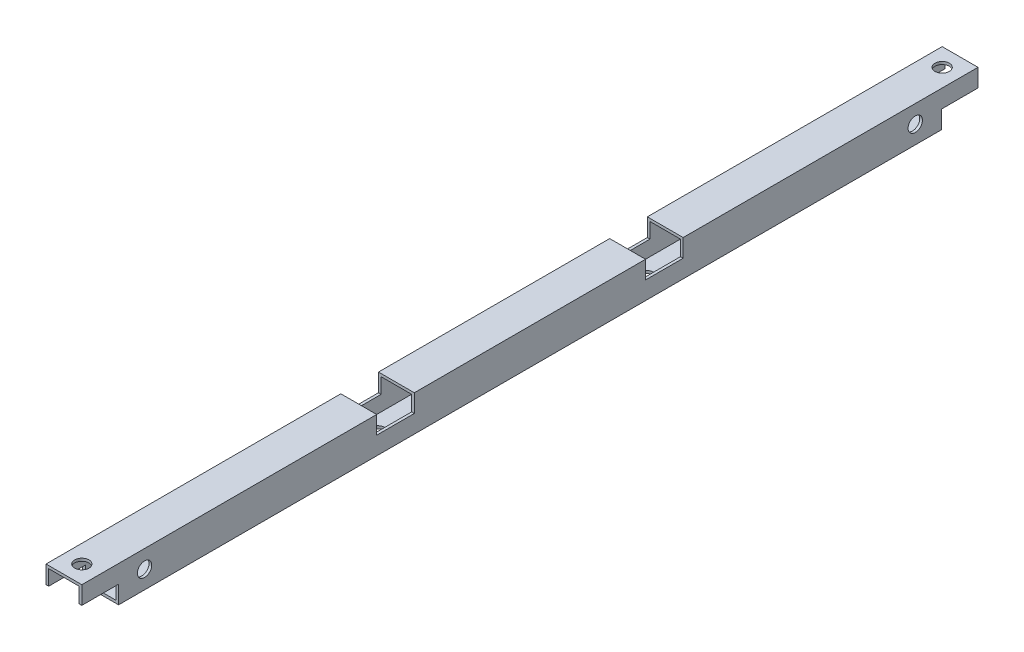
SolidWorks part; units mm, degrees
material "6063-O"
ref_plane "正面" through (0, 0, 0) normal (0, 0, 1) x (1, 0, 0)
ref_plane "平面" through (0, 0, 0) normal (0, 1, 0) x (1, 0, 0)
ref_plane "右側面" through (0, 0, 0) normal (1, 0, 0) x (0, 0, -1)
sketch "ｽｹｯﾁ1" plane through (0, 0, 0) normal (0, 0, 1) x (1, 0, 0)
  line L1 (-10, 10) -> (10, 10)
  line L2 (-10, 10) -> (-10, -10)
  line L3 (-10, -10) -> (10, -10)
  line L4 (10, 10) -> (10, -10)
  point P0 (0, 0)
  dimension "D1" = 20
  dimension "D2" = 20
extrude "ﾎﾞｽ - 押し出し1" add sketch "ｽｹｯﾁ1" along normal blind 500
ref_plane "平面1" through (0, 0, 250) normal (0, 0, 1) x (1, 0, 0)
ref_plane "平面2" through (0, 0, 325) normal (0, 0, 1) x (1, 0, 0)
sketch "ｽｹｯﾁ2" plane through (0, 0, 325) normal (0, 0, 1) x (1, 0, 0)
  line L0 (-10, 10) -> (-10, -10) construction
  line L1 (-10, 0) -> (10, 0)
  line L2 (-10, 0) -> (-10, 10)
  line L3 (-10, 10) -> (10, 10)
  line L4 (10, 0) -> (10, 10)
extrude "ｶｯﾄ - 押し出し1" cut sketch "ｽｹｯﾁ2" against normal mid plane 21
mirror "ﾐﾗｰ1" about plane through (0, 0, 250) normal (0, 0, 1) of "ｶｯﾄ - 押し出し1"
sketch "ｽｹｯﾁ3" plane through (0, -10, 0) normal (0, -1, 0) x (1, 0, 0)
  line L0 (-10, 185.5) -> (-10, 164.5) construction
  line L2 (10, 185.5) -> (-10, 185.5) construction
  line L3 (10, 314.5) -> (10, 335.5) construction
  line L4 (10, 314.5) -> (-10, 314.5) construction
  circle A0 centre (0, 325) radius 4
  circle A1 centre (0, 175) radius 4
  dimension "D2" = 10
  dimension "D1" = 10.5
  dimension "D3" = 10
  dimension "D4" = 10.5
  dimension "D5" = 8
  dimension "D6" = 8
extrude "ｶｯﾄ - 押し出し2" cut sketch "ｽｹｯﾁ3" against normal blind 21
sketch "ｽｹｯﾁ4" plane through (10, 0, 0) normal (1, 0, 0) x (0, 0, -1)
  line L1 (0, 0) -> (-20.5, 0)
  line L5 (-500, -10) -> (0, -10) construction
  line L7 (0, 0) -> (0, -10)
  line L8 (0, -10) -> (-20.5, -10)
  line L9 (-20.5, 0) -> (-20.5, -10)
  dimension "D1" = 20.5
extrude "ｶｯﾄ - 押し出し5" cut sketch "ｽｹｯﾁ4" against normal blind 21
sketch "ｽｹｯﾁ5" plane through (0, -10, 0) normal (0, -1, 0) x (1, 0, 0)
  line L0 (10, 260.25) -> (-55.5437, 260.25) construction
  line L1 (10, 500) -> (10, 20.5) construction
  circle A0 centre (0, 10) radius 4
  circle A1 centre (0, 510.5) radius 4
  dimension "D1" = 8
  dimension "D2" = 10
extrude "ｶｯﾄ - 押し出し4" cut sketch "ｽｹｯﾁ5" against normal blind 21
mirror "ﾐﾗｰ3" about plane through (0, 0, 250) normal (0, 0, 1) of "ｶｯﾄ - 押し出し5"
mirror "ﾐﾗｰ4" about plane through (0, 0, 250) normal (0, 0, 1) of "ｶｯﾄ - 押し出し4"
sketch "ｽｹｯﾁ6" plane through (10, 0, 0) normal (1, 0, 0) x (0, 0, -1)
  line L0 (0, 10) -> (0, 0) construction
  line L1 (-250, 10) -> (-250, -59.9158) construction
  line L2 (-314.5, 10) -> (-185.5, 10) construction
  circle A0 centre (-35, 0) radius 4
  circle A1 centre (-465, 0) radius 4
  dimension "D1" = 8
  dimension "D2" = 35
extrude "ｶｯﾄ - 押し出し6" cut sketch "ｽｹｯﾁ6" against normal through all
sketch "ｽｹｯﾁ7" plane through (0, 0, 0) normal (0, 0, -1) x (-1, 0, 0)
  line L0 (8.5, 8.5) -> (-8.5, 8.5)
  line L5 (-8.5, 8.5) -> (-8.5, -8.5)
  line L6 (8.5, -8.5) -> (-8.5, -8.5)
  line L7 (8.5, 8.5) -> (8.5, -8.5)
  point P0 (0, 0)
extrude "ｶｯﾄ - 押し出し7" cut sketch "ｽｹｯﾁ7" against normal through all
